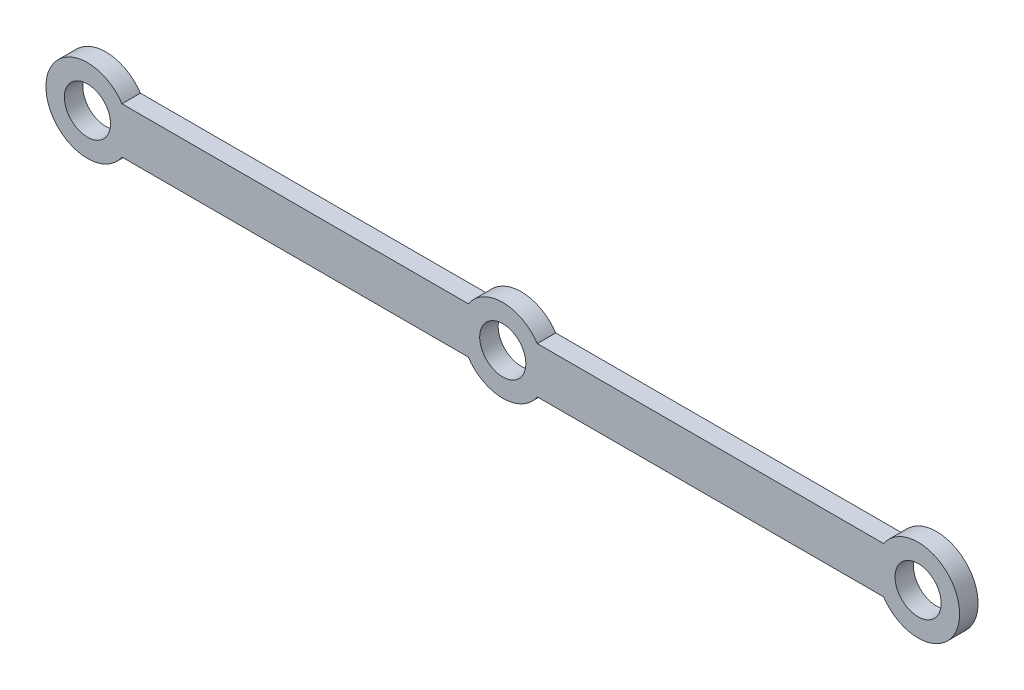
SolidWorks part; units mm, degrees
ref_plane "Front Plane" through (0, 0, 0) normal (0, 0, 1) x (1, 0, 0)
ref_plane "Top Plane" through (0, 0, 0) normal (0, 1, 0) x (1, 0, 0)
ref_plane "Right Plane" through (0, 0, 0) normal (1, 0, 0) x (0, 0, -1)
sketch "Sketch3" plane through (0, 0, 0) normal (0, 0, 1) x (1, 0, 0)
  line L1 (-41.2583, 2.5) -> (-3.7417, 2.5)
  line L2 (-41.2583, -2.5) -> (-3.7417, -2.5)
  line L3 (3.7417, 2.5) -> (41.2583, 2.5)
  line L4 (3.7417, -2.5) -> (41.2583, -2.5)
  circle A0 centre (-45, 0) radius 2.5
  arc A1 (-41.2583, 2.5) -> (-41.2583, -2.5) centre (-45, 0) ccw
  circle A2 centre (0, 0) radius 2.5
  arc A3 (-3.7417, -2.5) -> (3.7417, -2.5) centre (0, 0) ccw
  circle A4 centre (45, 0) radius 2.5
  circle A5 centre (45, 0) radius 2.5
  arc A6 (41.2583, -2.5) -> (41.2583, 2.5) centre (45, 0) ccw
  arc A7 (3.7417, 2.5) -> (-3.7417, 2.5) centre (0, 0) ccw
  point P16 (0, 0)
  point P17 (-42.5, 2.5)
  point P18 (42.5, 2.5)
  point P19 (-42.5, -2.5)
  point P20 (42.5, -2.5)
  dimension "D2" = 5
  dimension "D3" = 9
  dimension "D1" = 90
extrude "Boss-Extrude2" add sketch "Sketch3" along normal mid plane 2 contours L4 A6 L3 A7 L1 A1 L2 A3 | A0 | A2 | A4
